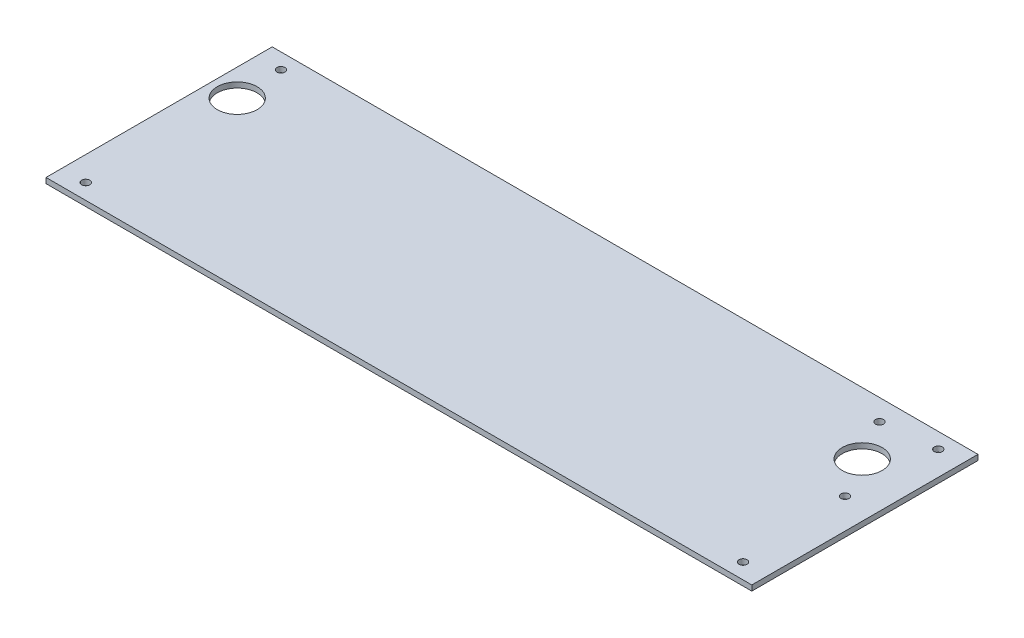
SolidWorks part; units mm, degrees
material "FR4"
ref_plane "前视基准面" through (0, 0, 0) normal (0, 0, 1) x (1, 0, 0)
ref_plane "上视基准面" through (0, 0, 0) normal (0, 1, 0) x (1, 0, 0)
ref_plane "右视基准面" through (0, 0, 0) normal (1, 0, 0) x (0, 0, -1)
sketch "草图1" plane through (0, 0, 0) normal (0, 1, 0) x (1, 0, 0)
  line L1 (131.05, -42) -> (-131.05, -42)
  line L2 (131.05, -42) -> (131.05, 42)
  line L3 (131.05, 42) -> (-131.05, 42)
  line L4 (-131.05, -42) -> (-131.05, 42)
  line L5 (131.05, -42) -> (-131.05, 42) construction
  line L6 (131.05, 42) -> (-131.05, -42) construction
  point P0 (0, 0)
  dimension "D1" = 262.1
  dimension "D2" = 84
extrude "凸台-拉伸1" add sketch "草图1" along normal mid plane 2
sketch "草图2" plane through (0, 1, 0) normal (0, 1, 0) x (1, 0, 0)
  line L0 (131.05, -42) -> (131.05, 42) construction
  line L1 (131.05, 29) -> (123.05, 29)
  line L2 (131.05, 29) -> (131.05, 9)
  line L3 (131.05, 9) -> (123.05, 9)
  line L4 (123.05, 29) -> (123.05, 9)
  line L5 (131.05, 19) -> (74.939, 19) construction
  line L6 (129.05, 29) -> (125.05, 29)
  line L7 (129.05, 29) -> (129.05, 34)
  line L8 (129.05, 34) -> (125.05, 34)
  line L9 (125.05, 29) -> (125.05, 34)
  line L10 (129.05, 9) -> (129.05, 4)
  line L11 (125.05, 9) -> (125.05, 4)
  line L12 (129.05, 4) -> (125.05, 4)
  line M12 (131.05, -42) -> (131.05, 42)
  dimension "D1" = 8
  dimension "D2" = 2
  dimension "D3" = 2
  dimension "D4" = 20
  dimension "D5" = 30
extrude "切除-拉伸1" [suppressed] cut sketch "草图2" against normal blind 10 contours L9 L1 L7 L8 | L5 L2 L1 L4 | L5 L4 L3 M12 | L12 L10 L3 L11
mirror "镜向1" [suppressed] about plane through (0, 0, 0) normal (1, 0, 0)
sketch "草图3" plane through (0, 1, 0) normal (0, 1, 0) x (1, 0, 0)
  line L1 (105.05, 26) -> (117.05, 26)
  line L2 (105.05, 26) -> (105.05, 12)
  line L3 (105.05, 12) -> (117.05, 12)
  line L4 (117.05, 26) -> (117.05, 12)
  line L5 (105.05, 26) -> (117.05, 12) construction
  line L6 (105.05, 12) -> (117.05, 26) construction
  circle A0 centre (111.05, 19) radius 4 construction
  dimension "D1" = 14
  dimension "D2" = 12
sketch "Sketch1" plane through (0, 1, 0) normal (0, 1, 0) x (1, 0, 0)
  line L0 (131.05, 42) -> (-131.05, 42) construction
  line L1 (-122.05, -36.25) -> (122.05, -36.25) construction
  line L2 (-122.05, -36.25) -> (-122.05, 36.25) construction
  line L3 (-122.05, 36.25) -> (122.05, 36.25) construction
  line L4 (122.05, -36.25) -> (122.05, 36.25) construction
  line L5 (-122.05, -36.25) -> (122.05, 36.25) construction
  line L6 (-122.05, 36.25) -> (122.05, -36.25) construction
  circle A0 centre (-122.05, 36.25) radius 1.5
  circle A1 centre (-122.05, -36.25) radius 1.5
  circle A2 centre (122.05, -36.25) radius 1.5
  circle A3 centre (122.05, 36.25) radius 1.5
  point P0 (0, 0)
  dimension "D3" = 3
  dimension "D1" = 244.1
  dimension "D2" = 5.75
extrude "Cut-Extrude1" cut sketch "Sketch1" against normal blind 10
sketch "Sketch2" plane through (0, 1, 0) normal (0, 1, 0) x (1, 0, 0)
  line L2 (0, 0) -> (0, 72.8508) construction
  line L3 (-131.05, 42) -> (-131.05, -42) construction
  line L4 (-131.05, 34) -> (-133.89, 34)
  line L5 (-131.05, 34) -> (-131.05, 4)
  line L6 (-131.05, 4) -> (-133.89, 4)
  line L7 (-137.89, 30) -> (-137.89, 8)
  line L8 (131.05, 42) -> (-131.05, 42) construction
  arc A0 (-133.89, 4) -> (-137.89, 8) centre (-133.89, 8) cw
  arc A1 (-137.89, 30) -> (-133.89, 34) centre (-133.89, 30) cw
  point P16 (-137.89, 4)
  point P19 (-137.89, 34)
  dimension "D4" = 4
  dimension "D1" = 8
  dimension "D2" = 6.84
  dimension "D3" = 30
extrude "Boss-Extrude1" [suppressed] add sketch "Sketch2" against normal blind 2
sketch "Sketch3" [suppressed] plane through (0, 1, 0) normal (0, 1, 0) x (1, 0, 0)
  line L0 (-126.05, 42) -> (-126.05, 34) construction
  line L1 (-128.39, 8.5) -> (-107.39, 8.5) construction
  line L2 (-128.39, 8.5) -> (-128.39, 29.5) construction
  line L3 (-128.39, 29.5) -> (-107.39, 29.5) construction
  line L4 (-107.39, 8.5) -> (-107.39, 29.5) construction
  line L5 (-128.39, 8.5) -> (-107.39, 29.5) construction
  line L6 (-128.39, 29.5) -> (-107.39, 8.5) construction
  line L8 (-132.89, 30) -> (-132.89, 8) construction
  circle A0 centre (-128.39, 29.5) radius 2
  circle A1 centre (-128.39, 8.5) radius 2
  circle A2 centre (-107.39, 8.5) radius 2
  circle A3 centre (-107.39, 29.5) radius 2
  point P0 (-117.89, 19)
  point P16 (-132.89, 19)
  dimension "D4" = 4
  dimension "D1" = 2.34
  dimension "D2" = 21
  dimension "D3" = 21
extrude "Cut-Extrude2" [suppressed] cut sketch "Sketch3" against normal blind 2
sketch "Sketch4" plane through (0, 1, 0) normal (0, 1, 0) x (1, 0, 0)
  circle A0 centre (-121.05, 19) radius 7 construction
  circle A1 centre (111.05, 19) radius 7 construction
  circle A6 centre (111.05, 19) radius 7 construction
  circle A7 centre (-121.05, 19) radius 7 construction
  circle A8 centre (-121.05, 19) radius 7.4
  circle A9 centre (111.05, 19) radius 7.4
  dimension "D1" = 0.4
extrude "Cut-Extrude3" cut sketch "Sketch4" against normal through all
sketch "Sketch5" plane through (0, 1, 0) normal (0, 1, 0) x (1, 0, 0)
  line L0 (111.05, 36.5) -> (111.05, 1.5)
  circle A0 centre (-121.05, 1.5) radius 1.5 construction
  circle A1 centre (-121.05, 36.5) radius 1.5 construction
  circle A4 centre (-121.05, 1.5) radius 1.5
  circle A5 centre (-121.05, 36.5) radius 1.5
  circle A6 centre (119.8, 3.8446) radius 1.5
  circle A7 centre (102.3, 34.1554) radius 1.5
extrude "Cut-Extrude4" cut sketch "Sketch5" against normal blind 10 contours A7 | A6
